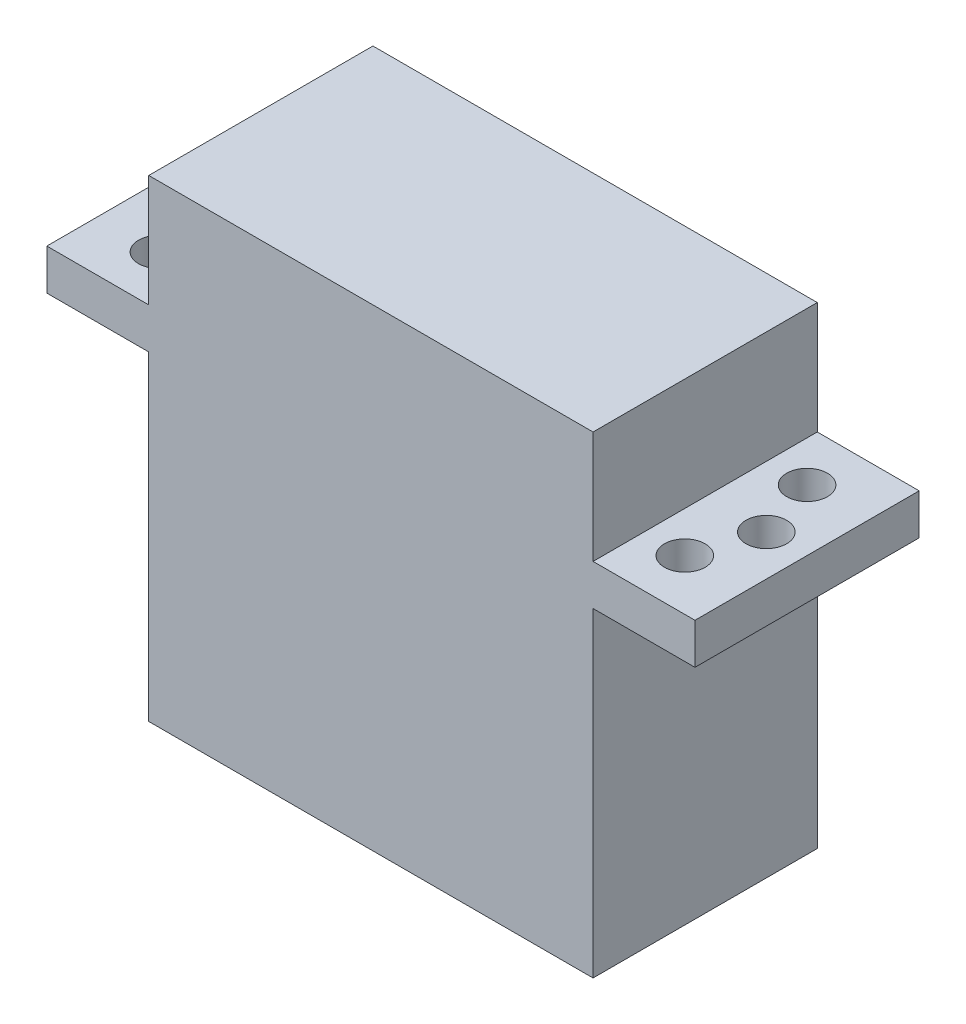
SolidWorks part; units mm, degrees
ref_plane "Front Plane" through (0, 0, 0) normal (0, 0, 1) x (1, 0, 0)
ref_plane "Top Plane" through (0, 0, 0) normal (0, 1, 0) x (1, 0, 0)
ref_plane "Right Plane" through (0, 0, 0) normal (1, 0, 0) x (0, 0, -1)
sketch "Sketch1" plane through (0, 0, 0) normal (0, 0, 1) x (1, 0, 0)
  line L0 (0, 12.7167) -> (0, -19.6453) construction
  line L1 (-23.0674, 0) -> (29.2357, 0) construction
  line L3 (10.9, -11.6) -> (-10.9, -11.6)
  line L4 (10.9, -11.6) -> (10.9, 11.6)
  line L5 (10.9, 11.6) -> (-10.9, 11.6)
  line L6 (-10.9, -11.6) -> (-10.9, 11.6)
  line L7 (10.9, -11.6) -> (-10.9, 11.6) construction
  line L8 (10.9, 11.6) -> (-10.9, -11.6) construction
  point P5 (0, 0)
  dimension "D1" = 21.8
  dimension "D2" = 23.2
extrude "Boss-Extrude1" add sketch "Sketch1" along normal mid plane 11
sketch "Sketch2" plane through (0, 11.6, 0) normal (0, 1, 0) x (1, 0, 0)
  line L0 (-23.9611, 0) -> (23.8636, 0) construction
  line L1 (0, 15.7753) -> (0, -15.1124) construction
  line L2 (10.9, 5.5) -> (-10.9, 5.5) construction
  line L3 (15.9, -5.5) -> (-15.9, -5.5)
  line L4 (15.9, -5.5) -> (15.9, 5.5)
  line L5 (15.9, 5.5) -> (-15.9, 5.5)
  line L6 (-15.9, -5.5) -> (-15.9, 5.5)
  line L7 (15.9, -5.5) -> (-15.9, 5.5) construction
  line L8 (15.9, 5.5) -> (-15.9, -5.5) construction
  point P5 (0, 0)
  point P10 (15.9, 5.5)
  dimension "D1" = 31.8
extrude "Boss-Extrude2" add sketch "Sketch2" against normal blind 2 from offset 5.5 offset against normal yes
sketch "Sketch3" plane through (0, 6.1, 0) normal (0, 1, 0) x (1, 0, 0)
  line L0 (-19.5479, 0) -> (19.5797, 0) construction
  line L1 (0, 11.8208) -> (0, -11.5669) construction
  line L2 (-12.9, 11.9466) -> (-12.9, -11.4412) construction
  circle A0 centre (-13.9, 0) radius 1
  circle A1 centre (-12.9, 3) radius 1
  circle A2 centre (-12.9, -3) radius 1
  circle A3 centre (12.9, -3) radius 1
  circle A4 centre (12.9, 3) radius 1
  circle A5 centre (13.9, 0) radius 1
  point P13 (-13.4972, -3.1258)
  point P14 (-12.1223, -3)
  point P15 (0, 0)
  point P16 (0, 0)
  dimension "D3" = 2
  dimension "D1" = 3
  dimension "D2" = 3
  dimension "D4" = 13.9
  dimension "D5" = 12.9
extrude "Cut-Extrude1" cut sketch "Sketch3" against normal through all
sketch "Sketch4" plane through (0, 11.6, 0) normal (0, 1, 0) x (1, 0, 0)
  line L0 (-25.7551, 0) -> (27.1328, 0) construction
  line L1 (0, 11.0592) -> (0, -14.2023) construction
  circle A0 centre (-5.1159, 0) radius 2.6878
